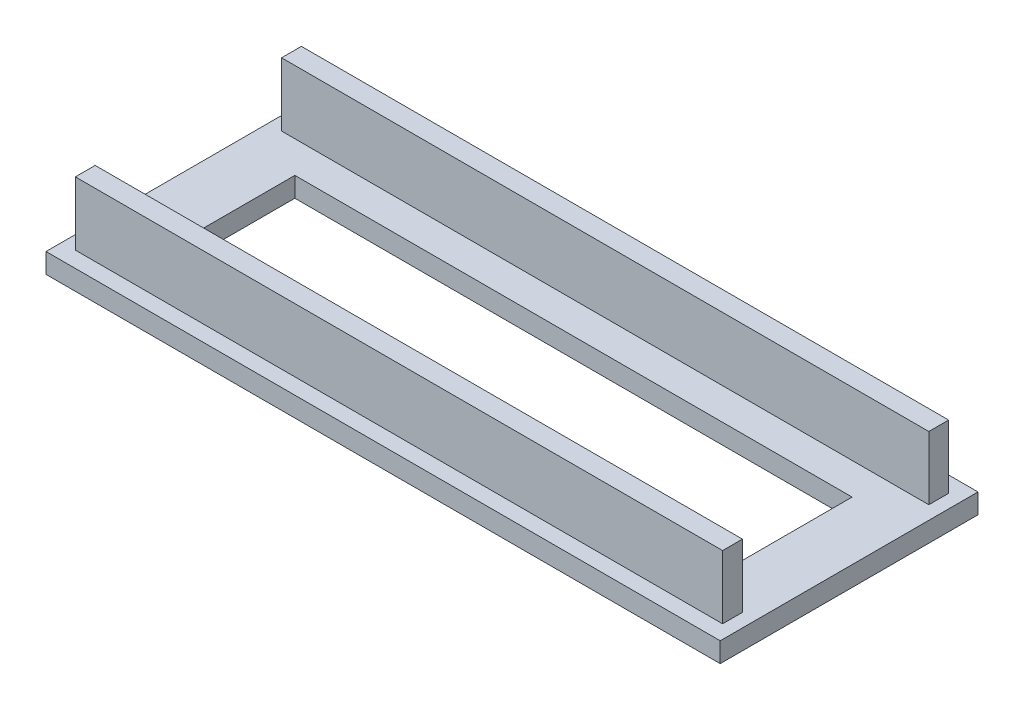
SolidWorks part; units mm, degrees
ref_plane "前视基准面" through (0, 0, 0) normal (0, 0, 1) x (1, 0, 0)
ref_plane "上视基准面" through (0, 0, 0) normal (0, 1, 0) x (1, 0, 0)
ref_plane "右视基准面" through (0, 0, 0) normal (1, 0, 0) x (0, 0, -1)
other "Configuration Table"
sketch "01_Rail_Base_Profile" plane through (0, 0, 0) normal (0, 1, 0) x (1, 0, 0)
  line L1 (-170, -65) -> (170, -65)
  line L2 (-170, -65) -> (-170, 65)
  line L3 (-170, 65) -> (170, 65)
  line L4 (170, -65) -> (170, 65)
  line L5 (-170, -65) -> (170, 65) construction
  line L6 (-170, 65) -> (170, -65) construction
  line L7 (-140.5, -31) -> (140.5, -31)
  line L8 (-140.5, -31) -> (-140.5, 31)
  line L9 (-140.5, 31) -> (140.5, 31)
  line L10 (140.5, -31) -> (140.5, 31)
  line L11 (-140.5, -31) -> (140.5, 31) construction
  line L12 (-140.5, 31) -> (140.5, -31) construction
  circle A0 centre (-145, -52) radius 4.5
  circle A1 centre (-145, 52) radius 4.5
  circle A2 centre (145, -52) radius 4.5
  circle A3 centre (145, 52) radius 4.5
  point P0 (0, 0)
  point P14 (0, 0)
extrude "01_Rail_Base" add sketch "01_Rail_Base_Profile" along normal blind 10
sketch "02_Guide_Rail_Profiles" plane through (0, 0, 0) normal (0, 1, 0) x (1, 0, 0)
  line L1 (-163.2, 47) -> (163.2, 47)
  line L2 (-163.2, 47) -> (-163.2, 57)
  line L3 (-163.2, 57) -> (163.2, 57)
  line L4 (163.2, 47) -> (163.2, 57)
  line L5 (-163.2, 47) -> (163.2, 57) construction
  line L6 (-163.2, 57) -> (163.2, 47) construction
  line L7 (-163.2, -57) -> (163.2, -57)
  line L8 (-163.2, -57) -> (-163.2, -47)
  line L9 (-163.2, -47) -> (163.2, -47)
  line L10 (163.2, -57) -> (163.2, -47)
  line L11 (-163.2, -57) -> (163.2, -47) construction
  line L12 (-163.2, -47) -> (163.2, -57) construction
  point P0 (0, 52)
  point P5 (0, -52)
extrude "02_Guide_Rails" add sketch "02_Guide_Rail_Profiles" along normal blind 42
